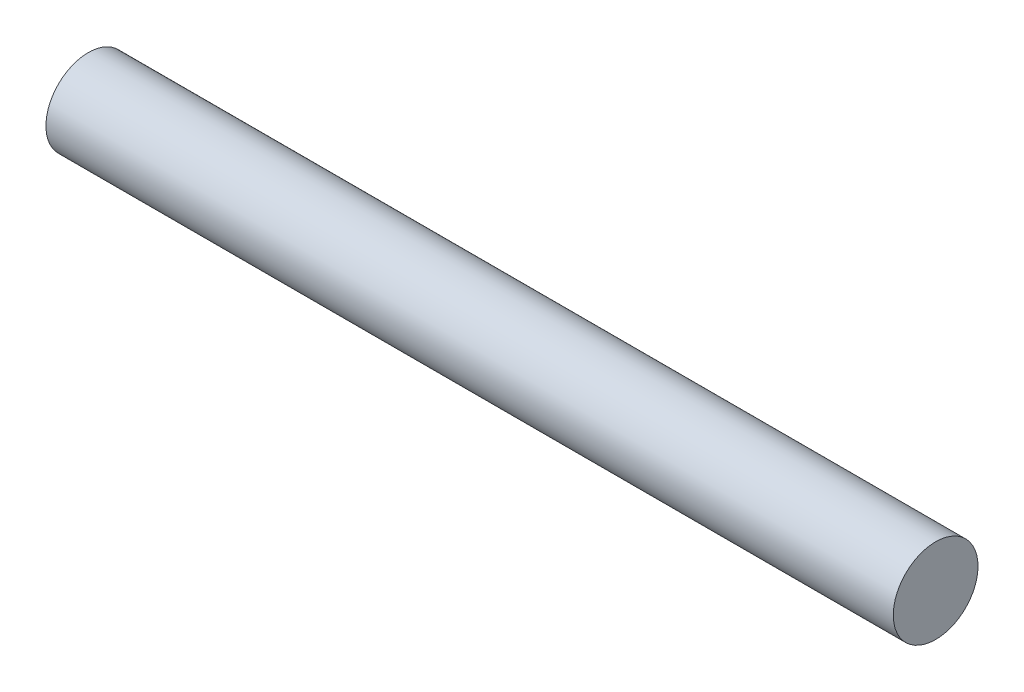
SolidWorks part; units mm, degrees
material "Cast Stainless Steel"
ref_plane "Front" through (0, 0, 0) normal (0, 0, 1) x (1, 0, 0)
ref_plane "Top" through (0, 0, 0) normal (0, 1, 0) x (1, 0, 0)
ref_plane "Right" through (0, 0, 0) normal (1, 0, 0) x (0, 0, -1)
sketch "Sketch1" plane through (0, 0, 0) normal (1, 0, 0) x (0, 0, -1)
  circle A0 centre (0, 0) radius 6.35
  dimension "D1" = 12.7
extrude "Boss-Extrude1" add sketch "Sketch1" along normal blind 127
